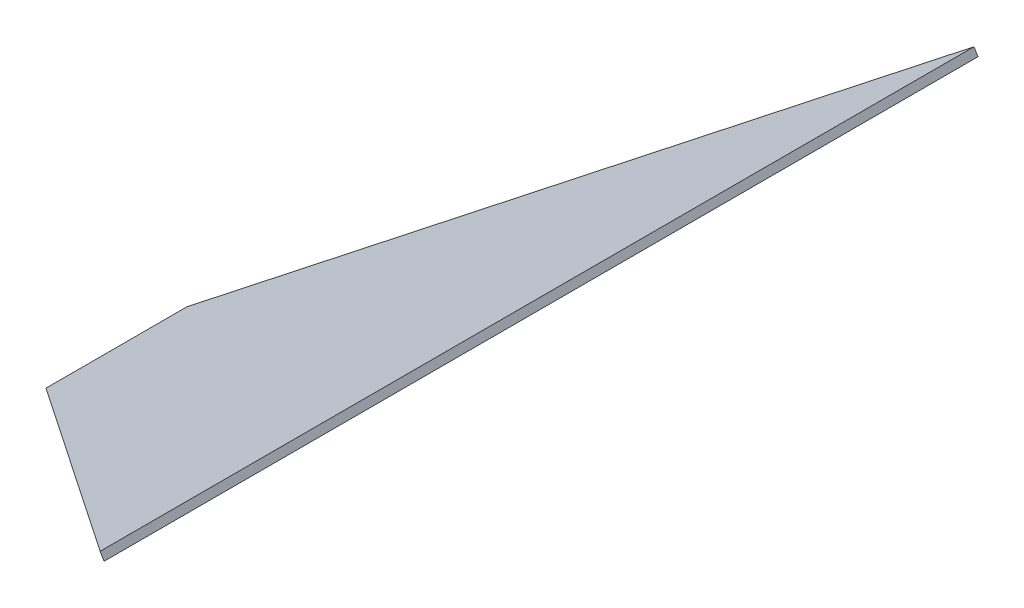
SolidWorks part; units mm, degrees
ref_plane "Front Plane" through (0, 0, 0) normal (0, 0, 1) x (1, 0, 0)
ref_plane "Top Plane" through (0, 0, 0) normal (0, 1, 0) x (1, 0, 0)
ref_plane "Right Plane" through (0, 0, 0) normal (1, 0, 0) x (0, 0, -1)
sketch "Sketch1" plane through (0, 0, 0) normal (0, 0, 1) x (1, 0, 0)
  line L0 (50, 38.1) -> (46.7853, 43.4599)
  line L2 (46.7853, 43.4599) -> (385.5853, 246.6599)
  line L3 (385.5853, 246.6599) -> (388.8, 241.3)
  line L10 (50, 38.1) -> (388.8, 241.3)
extrude "Boss-Extrude1" add sketch "Sketch1" along normal blind 711.2
sketch "Sketch3" plane through (-6.7927, 11.3257, 0) normal (-0.5143, 0.8576, 0) x (0.8576, 0.5143, 0)
  line L1 (62.4757, -412.3721) -> (457.5399, -707.5829)
  line L2 (62.4757, -412.3721) -> (62.4757, -711.2)
  line L4 (62.4757, -298.8279) -> (457.5399, -3.6171)
  line L5 (457.5399, -3.6171) -> (457.5399, 0)
  line L13 (457.5399, 0) -> (62.4757, 0)
  line L14 (62.4757, 0) -> (62.4757, -298.8279)
  line L15 (62.4757, -711.2) -> (457.5399, -711.2)
  line L16 (457.5399, -711.2) -> (457.5399, -707.5829)
extrude "Cut-Extrude1" cut sketch "Sketch3" against normal through all
